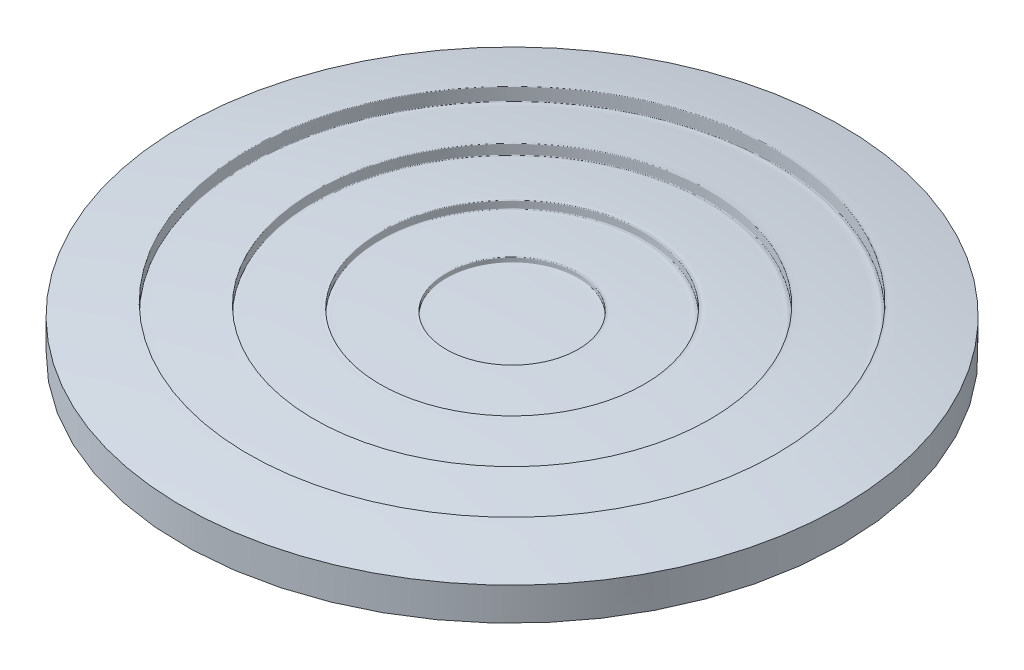
SolidWorks part; units mm, degrees
ref_plane "前视基准面" through (0, 0, 0) normal (0, 0, 1) x (1, 0, 0)
ref_plane "上视基准面" through (0, 0, 0) normal (0, 1, 0) x (1, 0, 0)
ref_plane "右视基准面" through (0, 0, 0) normal (1, 0, 0) x (0, 0, -1)
curve "曲线3"
  spline degree 3 poles (0, 0.08, 0) (0.0333, 0.08, 0) (0.1, 0.08, 0) (0.2, 0.0798, 0) (0.3, 0.0796, 0) (0.4, 0.0792, 0) (0.5, 0.0788, 0) (0.6, 0.0782, 0) (0.7, 0.0776, 0) (0.8, 0.0768, 0) (0.9, 0.076, 0) (1, 0.075, 0) (1.1, 0.074, 0) (1.2, 0.0728, 0) (1.3, 0.0716, 0) (1.4, 0.0702, 0) (1.5, 0.0688, 0) (1.6, 0.0672, 0) (1.7, 0.0656, 0) (1.8, 0.0638, 0) (1.9, 0.062, 0) (2, 0.06, 0) (2.1, 0.058, 0) (2.2, 0.0558, 0) (2.3, 0.0536, 0) (2.4, 0.0512, 0) (2.5, 0.0488, 0) (2.6, 0.0462, 0) (2.7, 0.0436, 0) (2.8, 0.0408, 0) (2.9, 0.038, 0) (3, 0.035, 0) (3.1, 0.032, 0) (3.2, 0.0288, 0) (3.3, 0.0256, 0) (3.4, 0.0222, 0) (3.4999, 0.0189, 0) (3.6003, 0.0149, 0) (3.699, 0.0126, 0) (3.8038, 0.0039, 0) (3.8859, 0.0186, 0) (4.0025, -0.0326, 0) (3.9999, 0.0101, 0) (4, 0.02, 0) (4, 0.03, 0) (4, 0.04, 0) (4, 0.05, 0) (4, 0.06, 0) (4, 0.07, 0) (4, 0.08, 0) (4, 0.09, 0) (4, 0.1, 0) (4, 0.11, 0) (4, 0.12, 0) (4, 0.13, 0) (4, 0.14, 0) (4, 0.15, 0) (4, 0.16, 0) (4, 0.17, 0) (4, 0.18, 0) (4, 0.19, 0) (4, 0.2, 0) (4, 0.21, 0) (4, 0.22, 0) (4, 0.23, 0) (4, 0.2368, 0) (3.9999, 0.2738, 0) (4.1154, 0.2204, 0) (4.1959, 0.2366, 0) (4.3011, 0.2269, 0) (4.3997, 0.224, 0) (4.5001, 0.2191, 0) (4.6, 0.2147, 0) (4.7, 0.21, 0) (4.8, 0.2053, 0) (4.9, 0.2004, 0) (5, 0.1955, 0) (5.1, 0.1904, 0) (5.2, 0.1852, 0) (5.3, 0.18, 0) (5.4, 0.1746, 0) (5.5, 0.1692, 0) (5.6, 0.1636, 0) (5.7, 0.1579, 0) (5.8, 0.1522, 0) (5.9, 0.1463, 0) (6, 0.1404, 0) (6.1, 0.1343, 0) (6.2, 0.1281, 0) (6.3, 0.1219, 0) (6.4, 0.1155, 0) (6.5, 0.1091, 0) (6.6, 0.1025, 0) (6.7, 0.0958, 0) (6.8, 0.0891, 0) (6.9, 0.0822, 0) (7, 0.0752, 0) (7.1, 0.0682, 0) (7.2, 0.061, 0) (7.3, 0.0537, 0) (7.4, 0.0463, 0) (7.4999, 0.039, 0) (7.6003, 0.031, 0) (7.699, 0.0247, 0) (7.8038, 0.0118, 0) (7.8859, 0.0232, 0) (8.0025, -0.0328, 0) (7.9999, 0.0102, 0) (8, 0.02, 0) (8, 0.03, 0) (8, 0.04, 0) (8, 0.05, 0) (8, 0.06, 0) (8, 0.07, 0) (8, 0.08, 0) (8, 0.09, 0) (8, 0.1, 0) (8, 0.11, 0) (8, 0.12, 0) (8, 0.13, 0) (8, 0.14, 0) (8, 0.15, 0) (8, 0.16, 0) (8, 0.17, 0) (8, 0.18, 0) (8, 0.19, 0) (8, 0.2, 0) (8, 0.21, 0) (8, 0.22, 0) (8, 0.23, 0) (8, 0.24, 0) (8, 0.25, 0) (8, 0.26, 0) (8, 0.27, 0) (8, 0.28, 0) (8, 0.29, 0) (8, 0.3, 0) (8, 0.31, 0) (8, 0.32, 0) (8, 0.33, 0) (8, 0.34, 0) (8, 0.35, 0) (8, 0.36, 0) (8, 0.37, 0) (8, 0.38, 0) (8, 0.39, 0) (8, 0.3973, 0) (7.9996, 0.4353, 0) (8.1151, 0.3777, 0) (8.196, 0.3903, 0) (8.3011, 0.3764, 0) (8.3997, 0.3695, 0) (8.5001, 0.3606, 0) (8.6, 0.3522, 0) (8.7, 0.3435, 0) (8.8, 0.3347, 0) (8.9, 0.3258, 0) (9, 0.3168, 0) (9.1, 0.3077, 0) (9.2, 0.2985, 0) (9.3, 0.2892, 0) (9.4, 0.2798, 0) (9.5, 0.2704, 0) (9.6, 0.2608, 0) (9.7, 0.2511, 0) (9.8, 0.2413, 0) (9.9, 0.2314, 0) (10, 0.2214, 0) (10.1, 0.2113, 0) (10.2, 0.2011, 0) (10.3, 0.1908, 0) (10.4, 0.1804, 0) (10.5, 0.1698, 0) (10.6, 0.1592, 0) (10.7, 0.1485, 0) (10.8, 0.1377, 0) (10.9, 0.1268, 0) (11, 0.1158, 0) (11.1, 0.1047, 0) (11.2, 0.0934, 0) (11.3, 0.0821, 0) (11.4, 0.0707, 0) (11.4999, 0.0593, 0) (11.6003, 0.0472, 0) (11.699, 0.037, 0) (11.8038, 0.0197, 0) (11.8859, 0.0279, 0) (12.0025, -0.0331, 0) (11.9999, 0.0102, 0) (12, 0.02, 0) (12, 0.03, 0) (12, 0.04, 0) (12, 0.05, 0) (12, 0.06, 0) (12, 0.07, 0) (12, 0.08, 0) (12, 0.09, 0) (12, 0.1, 0) (12, 0.11, 0) (12, 0.12, 0) (12, 0.13, 0) (12, 0.14, 0) (12, 0.15, 0) (12, 0.16, 0) (12, 0.17, 0) (12, 0.18, 0) (12, 0.19, 0) (12, 0.2, 0) (12, 0.21, 0) (12, 0.22, 0) (12, 0.23, 0) (12, 0.24, 0) (12, 0.25, 0) (12, 0.26, 0) (12, 0.27, 0) (12, 0.28, 0) (12, 0.29, 0) (12, 0.3, 0) (12, 0.31, 0) (12, 0.32, 0) (12, 0.33, 0) (12, 0.34, 0) (12, 0.35, 0) (12, 0.36, 0) (12, 0.37, 0) (12, 0.38, 0) (12, 0.39, 0) (12, 0.4, 0) (12, 0.41, 0) (12, 0.42, 0) (12, 0.43, 0) (12, 0.44, 0) (12, 0.45, 0) (12, 0.46, 0) (12, 0.47, 0) (12, 0.48, 0) (12, 0.49, 0) (12, 0.5, 0) (12, 0.51, 0) (12, 0.52, 0) (12, 0.53, 0) (12, 0.54, 0) (12, 0.55, 0) (12.0001, 0.5585, 0) (11.9987, 0.5989, 0) (12.1146, 0.5371, 0) (12.1961, 0.5457, 0) (12.3011, 0.5278, 0) (12.3997, 0.5169, 0) (12.5001, 0.5039, 0) (12.6, 0.4914, 0) (12.7, 0.4786, 0) (12.8, 0.4657, 0) (12.9, 0.4528, 0) (13, 0.4397, 0) (13.1, 0.4266, 0) (13.2, 0.4133, 0) (13.3, 0.3999, 0) (13.4, 0.3864, 0) (13.5, 0.3729, 0) (13.6, 0.3592, 0) (13.7, 0.3454, 0) (13.8, 0.3315, 0) (13.9, 0.3176, 0) (14, 0.3035, 0) (14.1, 0.2893, 0) (14.2, 0.275, 0) (14.3, 0.2606, 0) (14.4, 0.2461, 0) (14.5, 0.2315, 0) (14.6, 0.2168, 0) (14.7, 0.202, 0) (14.8, 0.1871, 0) (14.9, 0.172, 0) (15, 0.1569, 0) (15.1, 0.1417, 0) (15.2, 0.1264, 0) (15.3, 0.1109, 0) (15.4, 0.0954, 0) (15.4999, 0.0798, 0) (15.6003, 0.0637, 0) (15.699, 0.0494, 0) (15.8038, 0.0278, 0) (15.8859, 0.0327, 0) (16.0025, -0.0334, 0) (15.9999, 0.0102, 0) (16, 0.02, 0) (16, 0.03, 0) (16, 0.04, 0) (16, 0.05, 0) (16, 0.06, 0) (16, 0.07, 0) (16, 0.08, 0) (16, 0.09, 0) (16, 0.1, 0) (16, 0.11, 0) (16, 0.12, 0) (16, 0.13, 0) (16, 0.14, 0) (16, 0.15, 0) (16, 0.16, 0) (16, 0.17, 0) (16, 0.18, 0) (16, 0.19, 0) (16, 0.2, 0) (16, 0.21, 0) (16, 0.22, 0) (16, 0.23, 0) (16, 0.24, 0) (16, 0.25, 0) (16, 0.26, 0) (16, 0.27, 0) (16, 0.28, 0) (16, 0.29, 0) (16, 0.3, 0) (16, 0.31, 0) (16, 0.32, 0) (16, 0.33, 0) (16, 0.34, 0) (16, 0.35, 0) (16, 0.36, 0) (16, 0.37, 0) (16, 0.38, 0) (16, 0.39, 0) (16, 0.4, 0) (16, 0.41, 0) (16, 0.42, 0) (16, 0.43, 0) (16, 0.44, 0) (16, 0.45, 0) (16, 0.46, 0) (16, 0.47, 0) (16, 0.48, 0) (16, 0.49, 0) (16, 0.5, 0) (16, 0.51, 0) (16, 0.52, 0) (16, 0.53, 0) (16, 0.54, 0) (16, 0.55, 0) (16, 0.56, 0) (16, 0.57, 0) (16, 0.58, 0) (16, 0.59, 0) (16, 0.6, 0) (16, 0.61, 0) (16, 0.62, 0) (16, 0.63, 0) (16, 0.64, 0) (16, 0.65, 0) (16, 0.66, 0) (16, 0.67, 0) (16, 0.68, 0) (16, 0.69, 0) (16, 0.7, 0) (16, 0.71, 0) (16, 0.72, 0) (16, 0.7273, 0) (15.9996, 0.7657, 0) (16.1151, 0.6981, 0) (16.196, 0.7043, 0) (16.3011, 0.6818, 0) (16.3997, 0.6668, 0) (16.5001, 0.6497, 0) (16.6, 0.633, 0) (16.7, 0.6161, 0) (16.8, 0.5991, 0) (16.9, 0.582, 0) (17, 0.5648, 0) (17.1, 0.5475, 0) (17.2, 0.5301, 0) (17.3, 0.5126, 0) (17.4, 0.495, 0) (17.5, 0.4773, 0) (17.6, 0.4594, 0) (17.7, 0.4415, 0) (17.8, 0.4235, 0) (17.9, 0.4053, 0) (18, 0.3871, 0) (18.1, 0.3687, 0) (18.2, 0.3503, 0) (18.3, 0.3317, 0) (18.4, 0.3131, 0) (18.5, 0.2943, 0) (18.6, 0.2754, 0) (18.7, 0.2564, 0) (18.8, 0.2373, 0) (18.9, 0.2181, 0) (19, 0.1988, 0) (19.1, 0.1794, 0) (19.2, 0.1599, 0) (19.3, 0.1403, 0) (19.4, 0.1206, 0) (19.5, 0.1008, 0) (19.6, 0.0808, 0) (19.7, 0.0608, 0) (19.8, 0.0406, 0) (19.9, 0.0204, 0) (19.9667, 0.0068, 0) (20, 0, 0) knots 0 0 0 0 0.00453 0.00906 0.013589 0.018119 0.022649 0.027179 0.031709 0.036239 0.040768 0.045298 0.049828 0.054359 0.058889 0.063419 0.067949 0.072479 0.07701 0.08154 0.086071 0.090601 0.095132 0.099663 0.104194 0.108725 0.113256 0.117787 0.122319 0.12685 0.131382 0.135914 0.140445 0.144977 0.14951 0.154042 0.158574 0.163107 0.16764 0.172173 0.176706 0.181239 0.181692 0.182145 0.182598 0.183051 0.183504 0.183957 0.18441 0.184863 0.185316 0.185769 0.186222 0.186675 0.187128 0.187581 0.188034 0.188487 0.18894 0.189393 0.189846 0.190299 0.190752 0.191205 0.191658 0.192111 0.192132 0.196666 0.2012 0.205734 0.210268 0.214802 0.219336 0.223871 0.228406 0.232941 0.237476 0.242012 0.246548 0.251084 0.25562 0.260156 0.264693 0.26923 0.273768 0.278305 0.282843 0.287381 0.291919 0.296458 0.300997 0.305536 0.310076 0.314615 0.319156 0.323696 0.328237 0.332778 0.337319 0.341861 0.346403 0.350945 0.355488 0.360031 0.364575 0.369118 0.373663 0.374116 0.374569 0.375022 0.375475 0.375928 0.37638 0.376833 0.377286 0.377739 0.378192 0.378645 0.379098 0.379551 0.380004 0.380457 0.38091 0.381363 0.381816 0.382269 0.382722 0.383175 0.383628 0.384081 0.384534 0.384987 0.38544 0.385893 0.386346 0.386799 0.387252 0.387705 0.388158 0.388611 0.389064 0.389517 0.38997 0.390423 0.390876 0.391329 0.391782 0.391877 0.396421 0.400966 0.405511 0.410057 0.414603 0.419149 0.423696 0.428243 0.432791 0.437339 0.441888 0.446436 0.450986 0.455535 0.460086 0.464636 0.469187 0.473739 0.47829 0.482843 0.487396 0.491949 0.496503 0.501057 0.505612 0.510167 0.514723 0.519279 0.523835 0.528393 0.53295 0.537508 0.542067 0.546626 0.551186 0.555746 0.560307 0.564869 0.569431 0.573993 0.574446 0.574899 0.575352 0.575805 0.576258 0.576711 0.577164 0.577617 0.57807 0.578523 0.578976 0.579429 0.579882 0.580335 0.580788 0.581241 0.581694 0.582147 0.5826 0.583053 0.583506 0.583958 0.584411 0.584864 0.585317 0.58577 0.586223 0.586676 0.587129 0.587582 0.588035 0.588488 0.588941 0.589394 0.589847 0.5903 0.590753 0.591206 0.591659 0.592112 0.592565 0.593018 0.593471 0.593924 0.594377 0.59483 0.595283 0.595736 0.596189 0.596642 0.597095 0.597548 0.598001 0.598454 0.598907 0.59936 0.599617 0.60418 0.608744 0.613308 0.617873 0.622438 0.627004 0.63157 0.636137 0.640705 0.645273 0.649842 0.654412 0.658982 0.663552 0.668124 0.672696 0.677268 0.681841 0.686415 0.69099 0.695565 0.700141 0.704717 0.709294 0.713872 0.718451 0.72303 0.72761 0.73219 0.736772 0.741353 0.745936 0.75052 0.755104 0.759688 0.764274 0.76886 0.773447 0.778035 0.782624 0.783077 0.78353 0.783983 0.784436 0.784888 0.785341 0.785794 0.786247 0.7867 0.787153 0.787606 0.788059 0.788512 0.788965 0.789418 0.789871 0.790324 0.790777 0.79123 0.791683 0.792136 0.792589 0.793042 0.793495 0.793948 0.794401 0.794854 0.795307 0.79576 0.796213 0.796666 0.797119 0.797572 0.798025 0.798478 0.798931 0.799384 0.799837 0.80029 0.800743 0.801196 0.801649 0.802102 0.802555 0.803008 0.803461 0.803914 0.804366 0.804819 0.805272 0.805725 0.806178 0.806631 0.807084 0.807537 0.80799 0.808443 0.808896 0.809349 0.809802 0.810255 0.810708 0.811161 0.811614 0.812067 0.81252 0.812973 0.813426 0.813879 0.814332 0.814785 0.815238 0.815691 0.815787 0.820376 0.824966 0.829557 0.834148 0.838741 0.843334 0.847928 0.852522 0.857118 0.861714 0.866311 0.870909 0.875508 0.880107 0.884708 0.889309 0.893911 0.898514 0.903117 0.907722 0.912327 0.916934 0.921541 0.926149 0.930758 0.935367 0.939978 0.94459 0.949202 0.953815 0.95843 0.963045 0.967661 0.972278 0.976896 0.981515 0.986135 0.990756 0.995377 1 1 1 1
sketch "草图1" plane through (0, 0, 0) normal (0, 0, 1) x (1, 0, 0)
  line L0 (0, -1000) -> (0, 49000) construction
  line L1 (20, 0) -> (20, -2)
  line L2 (0, -2) -> (20, -2)
  line L3 (0, 0.08) -> (0, -2)
  spline S0 degree 3 poles (-49.7962, 2999.2754) (-34.7456, -5.6597) (-17.2872, 0.1071) (0.3333, 0.0796) (0.8334, 0.0774) (1.7334, 0.067) (2.5001, 0.0498) (3.0333, 0.0341) (3.1667, 0.0299) (3.3, 0.0256) (3.4, 0.0222) (3.4999, 0.0189) (3.6003, 0.0149) (3.699, 0.0126) (3.8038, 0.0039) (3.8859, 0.0186) (4.0025, -0.0326) (3.9999, 0.0101) (4, 0.02) (4, 0.03) (4, 0.04) (4, 0.0667) (4, 0.1167) (4, 0.17) (4, 0.2067) (4, 0.22) (4, 0.23) (4, 0.2368) (3.9999, 0.2738) (4.1154, 0.2204) (4.1959, 0.2366) (4.3011, 0.2269) (4.3997, 0.224) (4.5001, 0.2191) (4.6, 0.2147) (4.7, 0.21) (4.8667, 0.2021) (5.2001, 0.1856) (5.8669, 0.1495) (6.5002, 0.1099) (7, 0.0753) (7.1667, 0.0634) (7.3, 0.0537) (7.4, 0.0463) (7.4999, 0.039) (7.6003, 0.031) (7.699, 0.0247) (7.8038, 0.0118) (7.8859, 0.0232) (8.0025, -0.0328) (7.9999, 0.0102) (8, 0.02) (8, 0.03) (8, 0.04) (8, 0.0667) (8, 0.12) (8, 0.2167) (8, 0.3) (8, 0.3567) (8, 0.37) (8, 0.38) (8, 0.39) (8, 0.3973) (7.9996, 0.4353) (8.1151, 0.3777) (8.196, 0.3903) (8.3011, 0.3764) (8.3997, 0.3695) (8.5001, 0.3606) (8.6, 0.3522) (8.7, 0.3435) (8.8667, 0.3288) (9.2001, 0.2989) (9.867, 0.2359) (10.5003, 0.1706) (11, 0.1158) (11.1667, 0.0972) (11.3, 0.0821) (11.4, 0.0707) (11.4999, 0.0593) (11.6003, 0.0472) (11.699, 0.037) (11.8038, 0.0197) (11.8859, 0.0279) (12.0025, -0.0331) (11.9999, 0.0102) (12, 0.02) (12, 0.03) (12, 0.04) (12, 0.0667) (12, 0.12) (12, 0.2267) (12, 0.3533) (12, 0.4567) (12, 0.5067) (12, 0.52) (12, 0.53) (12, 0.54) (12, 0.55) (12.0001, 0.5585) (11.9987, 0.5989) (12.1146, 0.5371) (12.1961, 0.5457) (12.3011, 0.5278) (12.3997, 0.5169) (12.5001, 0.5039) (12.6, 0.4914) (12.7, 0.4786) (12.8667, 0.4572) (13.2001, 0.4136) (13.934, 0.3144) (14.6005, 0.2177) (15.1, 0.1417) (15.2, 0.1264) (15.3, 0.1109) (15.4, 0.0954) (15.4999, 0.0798) (15.6003, 0.0637) (15.699, 0.0494) (15.8038, 0.0278) (15.8859, 0.0327) (16.0025, -0.0334) (15.9999, 0.0102) (16, 0.02) (16, 0.03) (16, 0.04) (16, 0.0667) (16, 0.12) (16, 0.2267) (16, 0.4033) (16, 0.56) (16, 0.6667) (16, 0.6867) (16, 0.7) (16, 0.71) (16, 0.72) (16, 0.7273) (15.9996, 0.7657) (16.1151, 0.6981) (16.196, 0.7043) (16.3011, 0.6818) (16.3997, 0.6668) (16.5001, 0.6497) (16.6, 0.633) (16.7, 0.6161) (16.8667, 0.5878) (17.2002, 0.5304) (17.8673, 0.4126) (18.6675, 0.264) (19.3336, 0.1341) (19.6667, 0.0675) (19.8, 0.0406) (37.0571, -3.4534) (53.1107, -12.6966) (668.9301, 2928.5871) knots -2.3628 -2.3628 -2.3628 -2.3628 0.00453 0.00906 0.031709 0.072479 0.131382 0.135914 0.144977 0.14951 0.154042 0.158574 0.163107 0.16764 0.172173 0.176706 0.181239 0.181692 0.182145 0.182598 0.183051 0.183504 0.186222 0.189846 0.190752 0.191205 0.191658 0.192111 0.192132 0.196666 0.2012 0.205734 0.210268 0.214802 0.219336 0.223871 0.228406 0.242012 0.26923 0.319156 0.328237 0.337319 0.341861 0.346403 0.350945 0.355488 0.360031 0.364575 0.369118 0.373663 0.374116 0.374569 0.375022 0.375475 0.375928 0.378645 0.382722 0.389064 0.38997 0.390423 0.390876 0.391329 0.391782 0.391877 0.396421 0.400966 0.405511 0.410057 0.414603 0.419149 0.423696 0.428243 0.441888 0.469187 0.519279 0.528393 0.537508 0.542067 0.546626 0.551186 0.555746 0.560307 0.564869 0.569431 0.573993 0.574446 0.574899 0.575352 0.575805 0.576258 0.578976 0.583053 0.590753 0.596189 0.597095 0.597548 0.598001 0.598454 0.598907 0.59936 0.599617 0.60418 0.608744 0.613308 0.617873 0.622438 0.627004 0.63157 0.636137 0.649842 0.677268 0.736772 0.741353 0.745936 0.75052 0.755104 0.759688 0.764274 0.76886 0.773447 0.778035 0.782624 0.783077 0.78353 0.783983 0.784436 0.784888 0.787606 0.791683 0.799384 0.811614 0.812973 0.813879 0.814332 0.814785 0.815238 0.815691 0.815787 0.820376 0.824966 0.829557 0.834148 0.838741 0.843334 0.847928 0.852522 0.866311 0.893911 0.94459 0.976896 0.986135 0.990756 0.995377 3.378833 3.378833 3.378833 3.378833 only from (0, 0.08) to (20, 0) construction
  spline S1 degree 3 poles (0, 0.08) (0.0333, 0.08) (0.1, 0.08) (0.3333, 0.0796) (0.8334, 0.0774) (1.7334, 0.067) (2.5001, 0.0498) (3.0333, 0.0341) (3.1667, 0.0299) (3.3, 0.0256) (3.4, 0.0222) (3.4999, 0.0189) (3.6003, 0.0149) (3.699, 0.0126) (3.8038, 0.0039) (3.8859, 0.0186) (4.0025, -0.0326) (3.9999, 0.0101) (4, 0.02) (4, 0.03) (4, 0.04) (4, 0.0667) (4, 0.1167) (4, 0.17) (4, 0.2067) (4, 0.22) (4, 0.23) (4, 0.2368) (3.9999, 0.2738) (4.1154, 0.2204) (4.1959, 0.2366) (4.3011, 0.2269) (4.3997, 0.224) (4.5001, 0.2191) (4.6, 0.2147) (4.7, 0.21) (4.8667, 0.2021) (5.2001, 0.1856) (5.8669, 0.1495) (6.5002, 0.1099) (7, 0.0753) (7.1667, 0.0634) (7.3, 0.0537) (7.4, 0.0463) (7.4999, 0.039) (7.6003, 0.031) (7.699, 0.0247) (7.8038, 0.0118) (7.8859, 0.0232) (8.0025, -0.0328) (7.9999, 0.0102) (8, 0.02) (8, 0.03) (8, 0.04) (8, 0.0667) (8, 0.12) (8, 0.2167) (8, 0.3) (8, 0.3567) (8, 0.37) (8, 0.38) (8, 0.39) (8, 0.3973) (7.9996, 0.4353) (8.1151, 0.3777) (8.196, 0.3903) (8.3011, 0.3764) (8.3997, 0.3695) (8.5001, 0.3606) (8.6, 0.3522) (8.7, 0.3435) (8.8667, 0.3288) (9.2001, 0.2989) (9.867, 0.2359) (10.5003, 0.1706) (11, 0.1158) (11.1667, 0.0972) (11.3, 0.0821) (11.4, 0.0707) (11.4999, 0.0593) (11.6003, 0.0472) (11.699, 0.037) (11.8038, 0.0197) (11.8859, 0.0279) (12.0025, -0.0331) (11.9999, 0.0102) (12, 0.02) (12, 0.03) (12, 0.04) (12, 0.0667) (12, 0.12) (12, 0.2267) (12, 0.3533) (12, 0.4567) (12, 0.5067) (12, 0.52) (12, 0.53) (12, 0.54) (12, 0.55) (12.0001, 0.5585) (11.9987, 0.5989) (12.1146, 0.5371) (12.1961, 0.5457) (12.3011, 0.5278) (12.3997, 0.5169) (12.5001, 0.5039) (12.6, 0.4914) (12.7, 0.4786) (12.8667, 0.4572) (13.2001, 0.4136) (13.934, 0.3144) (14.6005, 0.2177) (15.1, 0.1417) (15.2, 0.1264) (15.3, 0.1109) (15.4, 0.0954) (15.4999, 0.0798) (15.6003, 0.0637) (15.699, 0.0494) (15.8038, 0.0278) (15.8859, 0.0327) (16.0025, -0.0334) (15.9999, 0.0102) (16, 0.02) (16, 0.03) (16, 0.04) (16, 0.0667) (16, 0.12) (16, 0.2267) (16, 0.4033) (16, 0.56) (16, 0.6667) (16, 0.6867) (16, 0.7) (16, 0.71) (16, 0.72) (16, 0.7273) (15.9996, 0.7657) (16.1151, 0.6981) (16.196, 0.7043) (16.3011, 0.6818) (16.3997, 0.6668) (16.5001, 0.6497) (16.6, 0.633) (16.7, 0.6161) (16.8667, 0.5878) (17.2002, 0.5304) (17.8673, 0.4126) (18.6675, 0.264) (19.3336, 0.1341) (19.6667, 0.0675) (19.8, 0.0406) (19.9, 0.0204) (19.9667, 0.0068) (20, 0) knots 0 0 0 0 0.00453 0.00906 0.031709 0.072479 0.131382 0.135914 0.144977 0.14951 0.154042 0.158574 0.163107 0.16764 0.172173 0.176706 0.181239 0.181692 0.182145 0.182598 0.183051 0.183504 0.186222 0.189846 0.190752 0.191205 0.191658 0.192111 0.192132 0.196666 0.2012 0.205734 0.210268 0.214802 0.219336 0.223871 0.228406 0.242012 0.26923 0.319156 0.328237 0.337319 0.341861 0.346403 0.350945 0.355488 0.360031 0.364575 0.369118 0.373663 0.374116 0.374569 0.375022 0.375475 0.375928 0.378645 0.382722 0.389064 0.38997 0.390423 0.390876 0.391329 0.391782 0.391877 0.396421 0.400966 0.405511 0.410057 0.414603 0.419149 0.423696 0.428243 0.441888 0.469187 0.519279 0.528393 0.537508 0.542067 0.546626 0.551186 0.555746 0.560307 0.564869 0.569431 0.573993 0.574446 0.574899 0.575352 0.575805 0.576258 0.578976 0.583053 0.590753 0.596189 0.597095 0.597548 0.598001 0.598454 0.598907 0.59936 0.599617 0.60418 0.608744 0.613308 0.617873 0.622438 0.627004 0.63157 0.636137 0.649842 0.677268 0.736772 0.741353 0.745936 0.75052 0.755104 0.759688 0.764274 0.76886 0.773447 0.778035 0.782624 0.783077 0.78353 0.783983 0.784436 0.784888 0.787606 0.791683 0.799384 0.811614 0.812973 0.813879 0.814332 0.814785 0.815238 0.815691 0.815787 0.820376 0.824966 0.829557 0.834148 0.838741 0.843334 0.847928 0.852522 0.866311 0.893911 0.94459 0.976896 0.986135 0.990756 0.995377 1 1 1 1
revolve "旋转1" add sketch "草图1" angle 360 about L0
